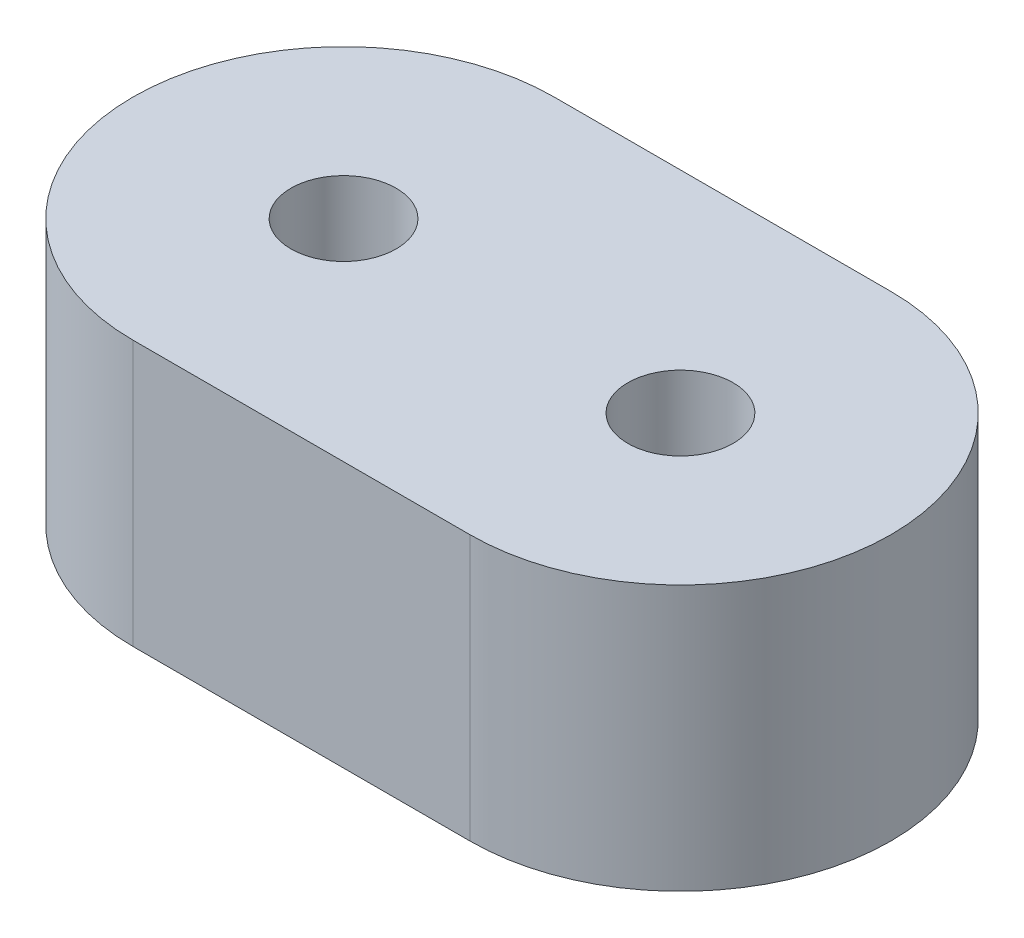
SolidWorks part; units mm, degrees
ref_plane "Front Plane" through (0, 0, 0) normal (0, 0, 1) x (1, 0, 0)
ref_plane "Top Plane" through (0, 0, 0) normal (0, 1, 0) x (1, 0, 0)
ref_plane "Right Plane" through (0, 0, 0) normal (1, 0, 0) x (0, 0, -1)
sketch "Sketch1" plane through (0, 0, 0) normal (0, 1, 0) x (1, 0, 0)
  line L0 (0, 5) -> (8, 5)
  line L1 (4, 5) -> (4, -5) construction
  line L2 (8, -5) -> (0, -5)
  circle A0 centre (0, 0) radius 1.25
  arc A1 (0, 5) -> (0, -5) centre (0, 0) ccw
  circle A2 centre (8, 0) radius 1.25
  arc A3 (8, 5) -> (8, -5) centre (8, 0) cw
  dimension "D1" = 2.5
  dimension "D2" = 5
  dimension "D3" = 4
extrude "Boss-Extrude1" add sketch "Sketch1" along normal blind 6.3
